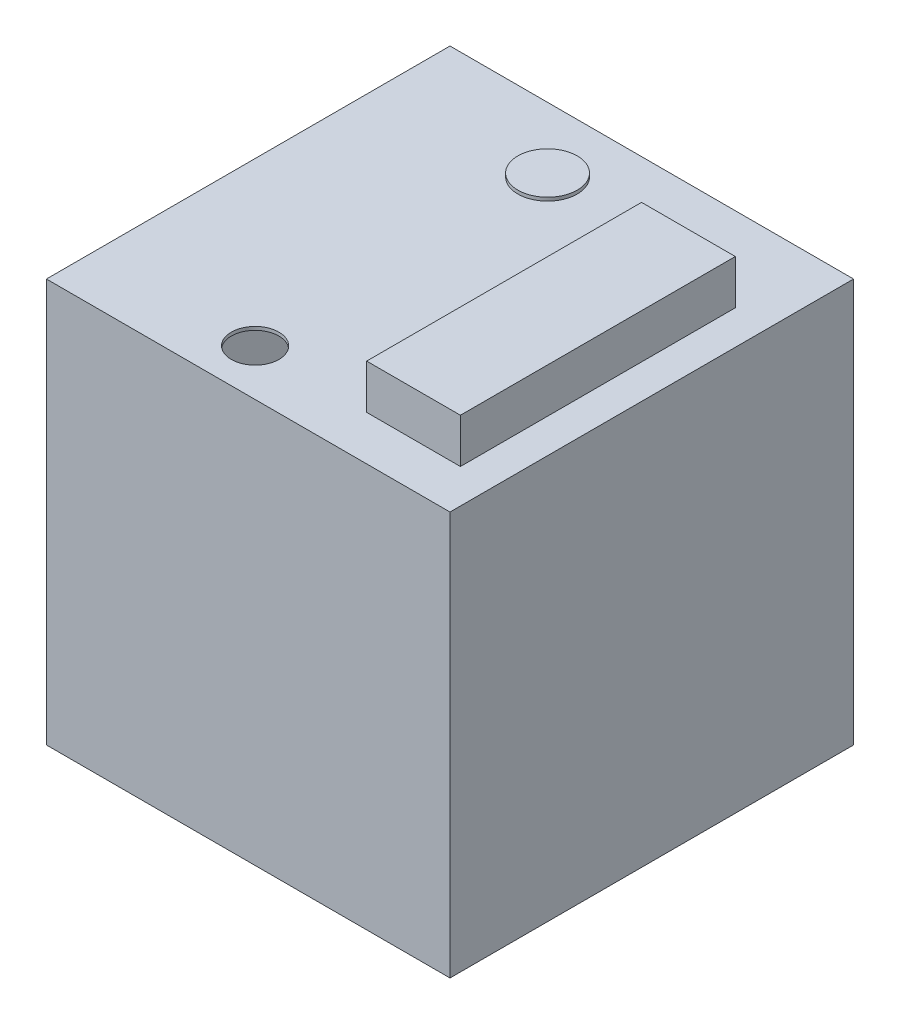
SolidWorks part; units mm, degrees
ref_plane "Front Plane" through (0, 0, 0) normal (0, 0, 1) x (1, 0, 0)
ref_plane "Top Plane" through (0, 0, 0) normal (0, 1, 0) x (1, 0, 0)
ref_plane "Right Plane" through (0, 0, 0) normal (1, 0, 0) x (0, 0, -1)
sketch "Sketch1" plane through (0, 0, 0) normal (0, 1, 0) x (1, 0, 0)
  line L1 (0, 0) -> (300, 0)
  line L2 (0, 0) -> (0, 300)
  line L3 (0, 300) -> (300, 300)
  line L4 (300, 0) -> (300, 300)
  dimension "D1" = 300
  dimension "D2" = 300
extrude "Boss-Extrude1" add sketch "Sketch1" along normal blind 300
shell "Shell1" thickness 2.54
sketch "Sketch2" plane through (0, 300, 0) normal (0, 1, 0) x (1, 0, 0)
  line L4 (0, 300) -> (0, 0)
  line L5 (0, 0) -> (300, 0)
  line L6 (300, 0) -> (300, 300)
  line L7 (300, 300) -> (0, 300)
  line L8 (0, 300) -> (0, 0)
  line L9 (0, 0) -> (300, 0)
  line L10 (300, 0) -> (300, 300)
  line L11 (300, 300) -> (0, 300)
  dimension "D1" = 0
extrude "Boss-Extrude2" add sketch "Sketch2" against normal blind 2.54
sketch "Sketch3" plane through (0, 300, 0) normal (0, 1, 0) x (1, 0, 0)
  circle A0 centre (241.5579, 57.9436) radius 15.8973
  circle A1 centre (241.5579, 206.6971) radius 16.202
  circle A2 centre (120.5544, 251.9579) radius 17.1918
  circle A3 centre (120.5544, 34.5658) radius 17.6611
extrude "Cut-Extrude1" cut sketch "Sketch3" against normal blind 2.54
sketch "Sketch4" plane through (0, 300, 0) normal (0, 1, 0) x (1, 0, 0)
  circle A0 centre (120.5544, 251.9579) radius 22.063
  circle A1 centre (241.5579, 206.6971) radius 19.9461
extrude "Boss-Extrude3" add sketch "Sketch4" along normal blind 2.54
sketch "Sketch5" plane through (0, 300, 0) normal (0, 1, 0) x (1, 0, 0)
  circle A0 centre (241.853, 150.8694) radius 19.0134
extrude "Cut-Extrude2" cut sketch "Sketch5" against normal blind 2.54
sketch "Sketch6" plane through (0, 300, 0) normal (0, 1, 0) x (1, 0, 0)
  line L1 (269.7431, 38.4081) -> (209.2778, 38.4081)
  line L2 (269.7431, 38.4081) -> (269.7431, 230.8743)
  line L3 (269.7431, 230.8743) -> (209.2778, 230.8743)
  line L4 (209.2778, 38.4081) -> (209.2778, 230.8743)
  line L5 (204.8845, 237.5063) -> (274.5886, 237.5063)
  line L6 (204.8845, 237.5063) -> (204.8845, 33.1588)
  line L7 (204.8845, 33.1588) -> (274.5886, 33.1588)
  line L8 (274.5886, 237.5063) -> (274.5886, 33.1588)
extrude "Boss-Extrude4" add sketch "Sketch6" along normal blind 30.48
sketch "Sketch7" plane through (0, 330.48, 0) normal (0, 1, 0) x (1, 0, 0)
  line L4 (204.8845, 237.5063) -> (204.8845, 33.1588)
  line L5 (204.8845, 33.1588) -> (274.5886, 33.1588)
  line L6 (274.5886, 33.1588) -> (274.5886, 237.5063)
  line L7 (274.5886, 237.5063) -> (204.8845, 237.5063)
  line L8 (204.8845, 237.5063) -> (204.8845, 33.1588)
  line L9 (204.8845, 33.1588) -> (274.5886, 33.1588)
  line L10 (274.5886, 33.1588) -> (274.5886, 237.5063)
  line L11 (274.5886, 237.5063) -> (204.8845, 237.5063)
  dimension "D1" = 0
extrude "Boss-Extrude5" add sketch "Sketch7" along normal blind 2.54
